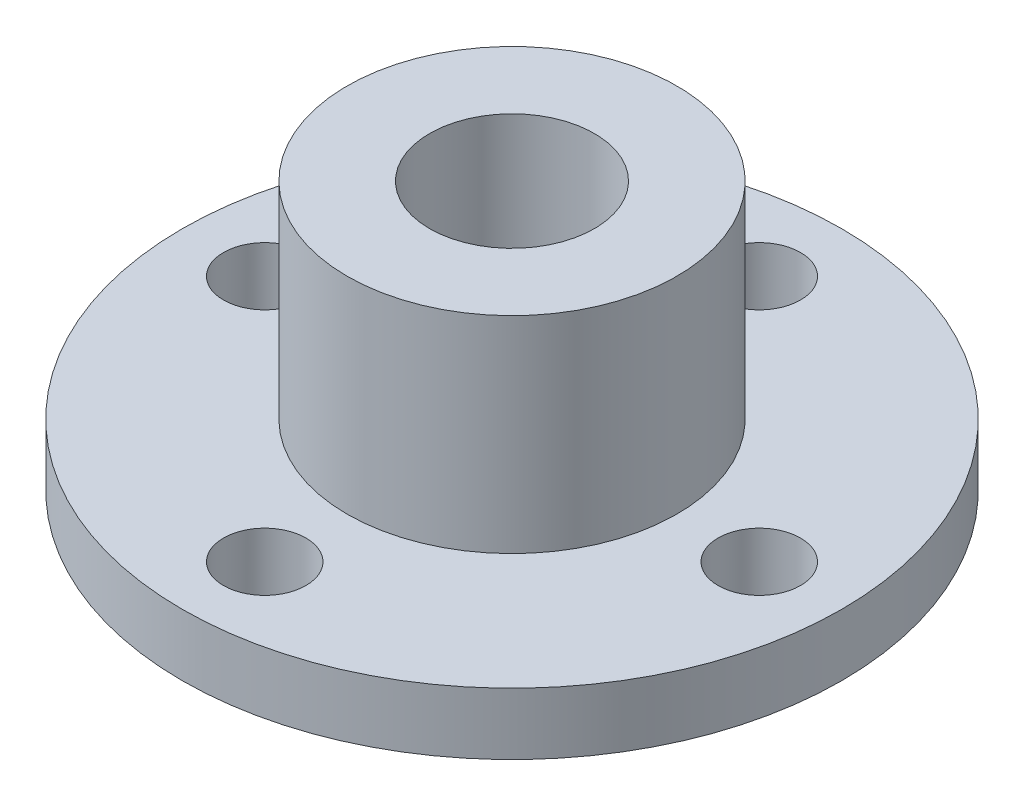
SolidWorks part; units mm, degrees
ref_plane "前视基准面" through (0, 0, 0) normal (0, 0, 1) x (1, 0, 0)
ref_plane "上视基准面" through (0, 0, 0) normal (0, 1, 0) x (1, 0, 0)
ref_plane "右视基准面" through (0, 0, 0) normal (1, 0, 0) x (0, 0, -1)
sketch "草图1" plane through (0, 0, 0) normal (0, 1, 0) x (1, 0, 0)
  circle A0 centre (0, 0) radius 16
  dimension "D1" = 32
extrude "凸台-拉伸1" add sketch "草图1" along normal blind 3
sketch "草图2" plane through (0, 3, 0) normal (0, 1, 0) x (1, 0, 0)
  circle A0 centre (0, 0) radius 8
  dimension "D1" = 16
extrude "凸台-拉伸2" add sketch "草图2" along normal blind 10
sketch "草图3" plane through (0, 13, 0) normal (0, 1, 0) x (1, 0, 0)
  circle A0 centre (0, 0) radius 4
  dimension "D1" = 8
extrude "切除-拉伸1" cut sketch "草图3" against normal up to surface (13 mm away) up to face at (0, 0, 16)
sketch "草图4" plane through (0, 0, 0) normal (0, -1, 0) x (1, 0, 0)
  line L0 (0, 0) -> (34.833, 0) construction
  line L1 (0, 0) -> (0, 14.1524) construction
  circle A0 centre (0, 0) radius 12
  circle A1 centre (0, 12) radius 2
  circle A2 centre (12, 0) radius 2
  circle A3 centre (0, -12) radius 2
  circle A4 centre (-12, 0) radius 2
  dimension "D1" = 24
  dimension "D2" = 4
extrude "切除-拉伸2" cut sketch "草图4" against normal up to surface (3 mm away) contours A4 | A1 | A2 | A3 up to face at (0, 3, 8)
